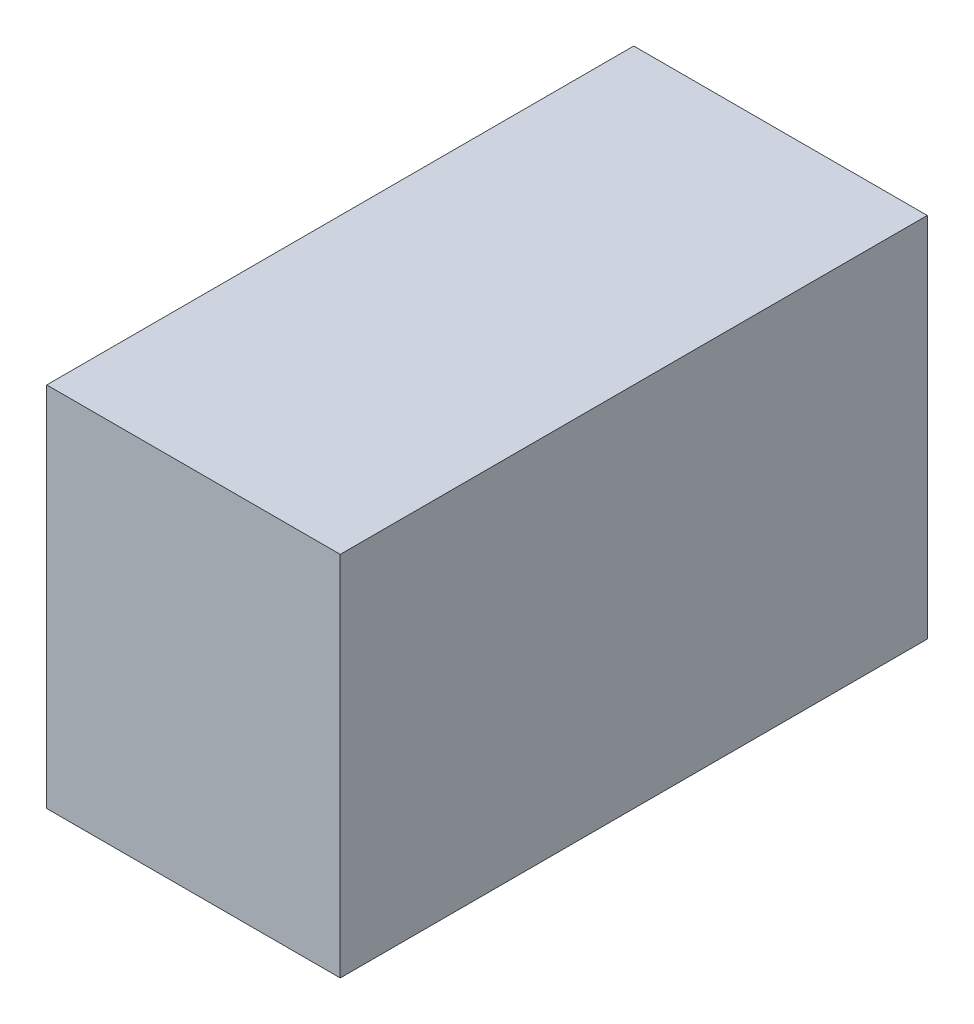
SolidWorks part; units mm, degrees
ref_plane "Front Plane" through (0, 0, 0) normal (0, 0, 1) x (1, 0, 0)
ref_plane "Top Plane" through (0, 0, 0) normal (0, 1, 0) x (1, 0, 0)
ref_plane "Right Plane" through (0, 0, 0) normal (1, 0, 0) x (0, 0, -1)
sketch "Sketch1" plane through (0, 0, 0) normal (0, 0, 1) x (1, 0, 0)
  line L1 (101.6, -127) -> (-101.6, -127)
  line L2 (101.6, -127) -> (101.6, 127)
  line L3 (101.6, 127) -> (-101.6, 127)
  line L4 (-101.6, -127) -> (-101.6, 127)
  line L5 (101.6, -127) -> (-101.6, 127) construction
  line L6 (101.6, 127) -> (-101.6, -127) construction
  point P0 (0, 0)
  dimension "D1" = 254
  dimension "D2" = 203.2
extrude "Boss-Extrude1" add sketch "Sketch1" along normal blind 406.4
